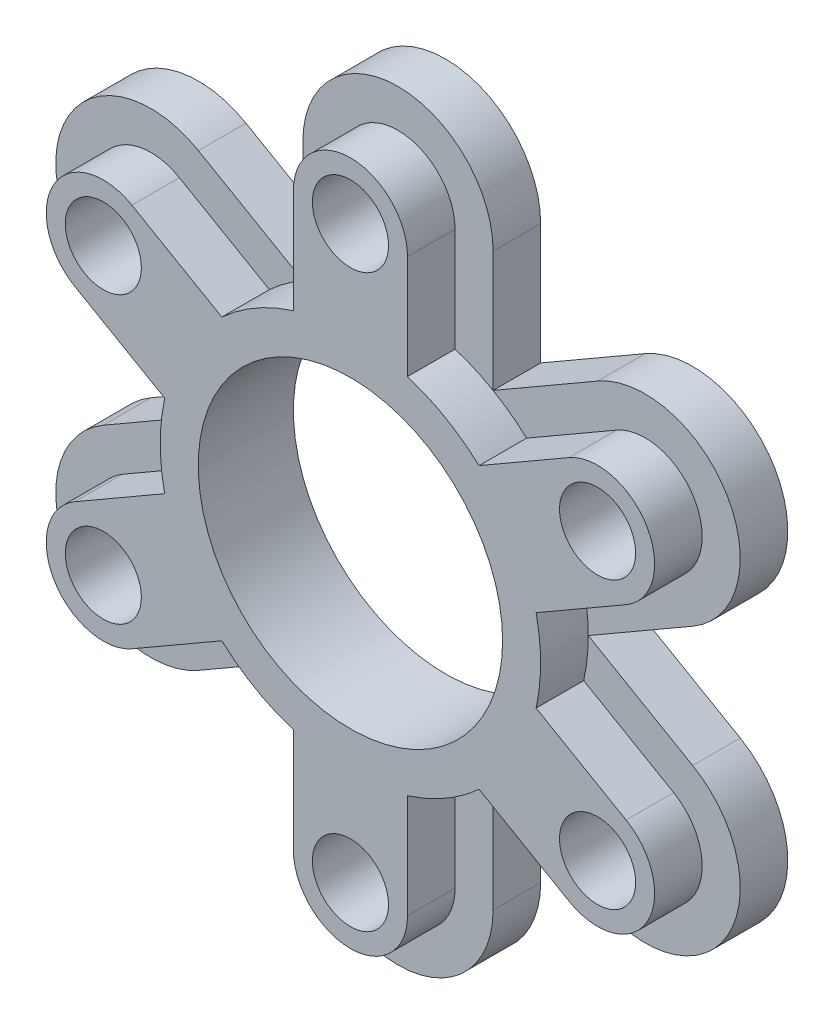
SolidWorks part; units mm, degrees
ref_plane "Front Plane" through (0, 0, 0) normal (0, 0, 1) x (1, 0, 0)
ref_plane "Top Plane" through (0, 0, 0) normal (0, 1, 0) x (1, 0, 0)
ref_plane "Right Plane" through (0, 0, 0) normal (1, 0, 0) x (0, 0, -1)
sketch "Sketch2" plane through (0, 0, 0) normal (0, 0, 1) x (1, 0, 0)
  line L0 (0, 30) -> (0, -30) construction
  line L1 (10, 30) -> (10, 17.3205)
  line L2 (-10, 30) -> (-10, 17.3205)
  line L3 (20.9808, 23.6603) -> (10, 17.3205)
  line L4 (30.9808, 6.3397) -> (20, 0)
  line L5 (30.9808, -6.3397) -> (20, 0)
  line L6 (20.9808, -23.6603) -> (10, -17.3205)
  line L7 (10, -30) -> (10, -17.3205)
  line L8 (-10, -30) -> (-10, -17.3205)
  line L9 (-20.9808, -23.6603) -> (-10, -17.3205)
  line L10 (-30.9808, -6.3397) -> (-20, 0)
  line L11 (-30.9808, 6.3397) -> (-20, 0)
  line L12 (-20.9808, 23.6603) -> (-10, 17.3205)
  circle A0 centre (0, 0) radius 16
  circle A1 centre (0, 0) radius 20 construction
  arc A4 (10, 30) -> (-10, 30) centre (0, 30) ccw
  arc A6 (30.9808, 6.3397) -> (20.9808, 23.6603) centre (25.9808, 15) ccw
  arc A7 (20.9808, -23.6603) -> (30.9808, -6.3397) centre (25.9808, -15) ccw
  arc A8 (-10, -30) -> (10, -30) centre (0, -30) ccw
  arc A9 (-30.9808, -6.3397) -> (-20.9808, -23.6603) centre (-25.9808, -15) ccw
  arc A10 (-20.9808, 23.6603) -> (-30.9808, 6.3397) centre (-25.9808, 15) ccw
  circle A11 centre (0, 30) radius 4
  circle A12 centre (25.9808, 15) radius 4
  circle A13 centre (25.9808, -15) radius 4
  circle A14 centre (0, -30) radius 4
  circle A15 centre (-25.9808, -15) radius 4
  circle A16 centre (-25.9808, 15) radius 4
  point P6 (0, 0)
  point P39 (0, 0)
  point P44 (0, 0)
  dimension "D1" = 32
  dimension "D2" = 40
  dimension "D3" = 60
  dimension "D5" = 8
  dimension "D6" = 6
  dimension "D4" = 6
extrude "Boss-Extrude6" add sketch "Sketch2" along normal blind 5
sketch "Sketch3" plane through (0, 0, 5) normal (0, 0, 1) x (1, 0, 0)
  line L0 (-6, 30) -> (-6, 19.0788)
  line L1 (6, 30) -> (6, 19.0788)
  line L2 (22.9808, 20.1962) -> (13.5227, 14.7355)
  line L3 (28.9808, 9.8038) -> (19.5227, 4.3432)
  line L4 (28.9808, -9.8038) -> (19.5227, -4.3432)
  line L5 (22.9808, -20.1962) -> (13.5227, -14.7355)
  line L6 (6, -30) -> (6, -19.0788)
  line L7 (-6, -30) -> (-6, -19.0788)
  line L8 (-22.9808, -20.1962) -> (-13.5227, -14.7355)
  line L9 (-28.9808, -9.8038) -> (-19.5227, -4.3432)
  line L10 (-28.9808, 9.8038) -> (-19.5227, 4.3432)
  line L11 (-22.9808, 20.1962) -> (-13.5227, 14.7355)
  arc A0 (-6, 19.0788) -> (-13.5227, 14.7355) centre (0, 0) ccw
  arc A1 (6, 30) -> (-6, 30) centre (0, 30) ccw
  circle A2 centre (0, 30) radius 4
  arc A3 (28.9808, 9.8038) -> (22.9808, 20.1962) centre (25.9808, 15) ccw
  circle A4 centre (25.9808, 15) radius 4
  arc A5 (22.9808, -20.1962) -> (28.9808, -9.8038) centre (25.9808, -15) ccw
  circle A6 centre (25.9808, -15) radius 4
  arc A7 (-6, -30) -> (6, -30) centre (0, -30) ccw
  circle A8 centre (0, -30) radius 4
  arc A9 (-28.9808, -9.8038) -> (-22.9808, -20.1962) centre (-25.9808, -15) ccw
  circle A10 centre (-25.9808, -15) radius 4
  arc A11 (-22.9808, 20.1962) -> (-28.9808, 9.8038) centre (-25.9808, 15) ccw
  circle A12 centre (-25.9808, 15) radius 4
  arc A13 (-19.5227, 4.3432) -> (-19.5227, -4.3432) centre (0, 0) ccw
  arc A14 (-13.5227, -14.7355) -> (-6, -19.0788) centre (0, 0) ccw
  arc A15 (6, -19.0788) -> (13.5227, -14.7355) centre (0, 0) ccw
  arc A16 (19.5227, -4.3432) -> (19.5227, 4.3432) centre (0, 0) ccw
  arc A17 (13.5227, 14.7355) -> (6, 19.0788) centre (0, 0) ccw
  circle A18 centre (0, 0) radius 16
  point P43 (0, 0)
  dimension "D1" = 6
  dimension "D2" = 8
  dimension "D3" = 6
extrude "Boss-Extrude7" add sketch "Sketch3" along normal blind 5
